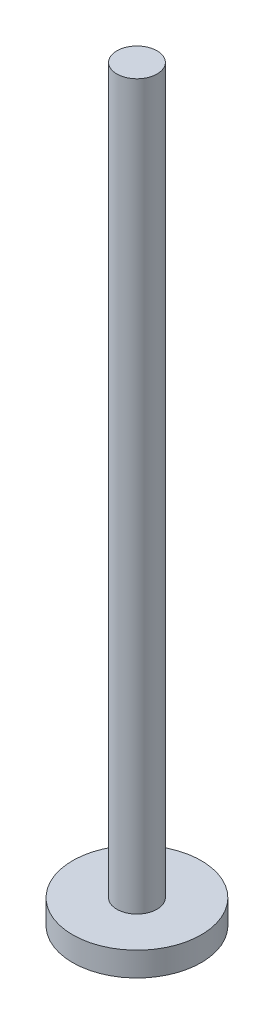
SolidWorks part; units mm, degrees
material "6061-T6 (SS)"
ref_plane "前视基准面" through (0, 0, 0) normal (0, 0, 1) x (1, 0, 0)
ref_plane "上视基准面" through (0, 0, 0) normal (0, 1, 0) x (1, 0, 0)
ref_plane "右视基准面" through (0, 0, 0) normal (1, 0, 0) x (0, 0, -1)
sketch "草图1" plane through (0, 0, 0) normal (0, 1, 0) x (1, 0, 0)
  circle A0 centre (0, 0) radius 8
  dimension "D1" = 16
extrude "凸台-拉伸1" add sketch "草图1" along normal blind 3
sketch "草图2" plane through (0, 3, 0) normal (0, 1, 0) x (1, 0, 0)
  circle A0 centre (0, 0) radius 2.5
  dimension "D1" = 5
extrude "凸台-拉伸2" add sketch "草图2" along normal blind 90
equation "\"行程L\"= 50"
equation "\"D1@凸台-拉伸2\"=\"行程L\"+50"
